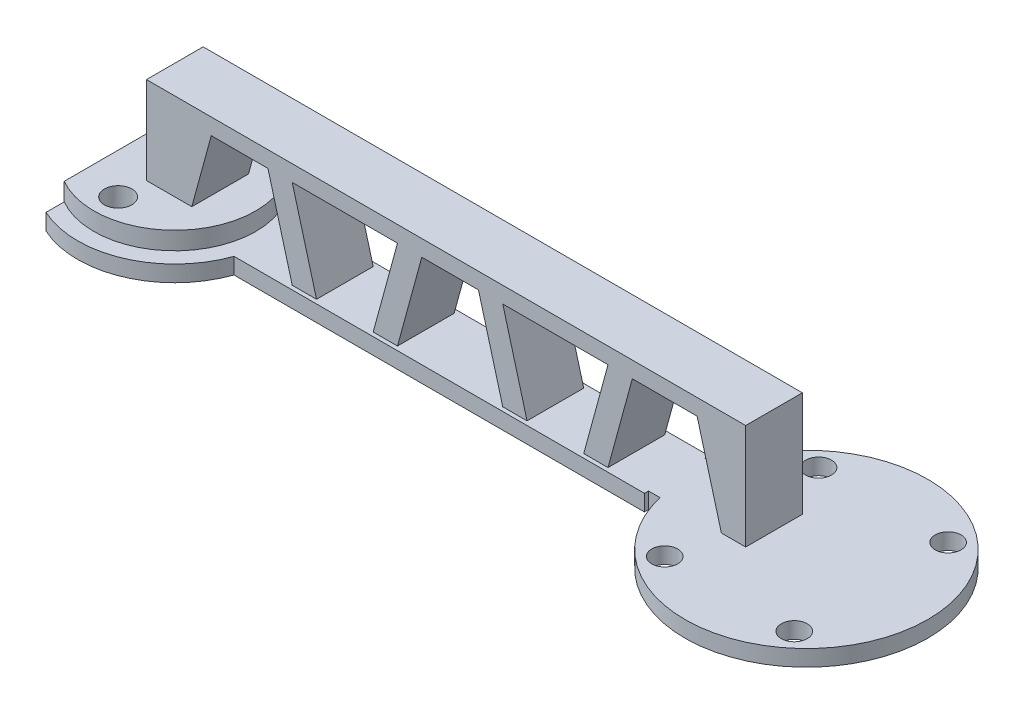
SolidWorks part; units mm, degrees
ref_plane "前视基准面" through (0, 0, 0) normal (0, 0, 1) x (1, 0, 0)
ref_plane "上视基准面" through (0, 0, 0) normal (0, 1, 0) x (1, 0, 0)
ref_plane "右视基准面" through (0, 0, 0) normal (1, 0, 0) x (0, 0, -1)
other "Configuration Table"
sketch "草图1" plane through (0, 0, 0) normal (0, 1, 0) x (1, 0, 0)
  line L0 (0, -4) -> (62, -4)
  line L1 (62, -4) -> (62, 4)
  line L2 (62, 4) -> (0, 4)
  line L3 (0, 4) -> (0, -4)
extrude "凸台-拉伸1" add sketch "草图1" along normal blind 2
sketch "草图2" plane through (0, 0, 0) normal (0, 1, 0) x (1, 0, 0)
  circle A0 centre (0, 0) radius 12
  circle A1 centre (0, -7) radius 1.7
  circle A2 centre (0, 7) radius 1.7
extrude "凸台-拉伸2" add sketch "草图2" along normal blind 2
sketch "草图3" plane through (0, 0, 0) normal (0, 1, 0) x (1, 0, 0)
  circle A0 centre (0, 0) radius 10
  circle A1 centre (0, -7) radius 1.7
  circle A2 centre (0, 7) radius 1.7
extrude "凸台-拉伸3" add sketch "草图3" along normal blind 2.2 from offset 2
sketch "草图4" plane through (0, 0, 0) normal (0, 1, 0) x (1, 0, 0)
  line L0 (-10, -3.5) -> (10, -3.5)
  line L1 (10, -3.5) -> (10, 3.5)
  line L2 (10, 3.5) -> (-10, 3.5)
  line L3 (-10, 3.5) -> (-10, -3.5)
  dimension "D1" = 3.5
  dimension "D2" = 3.5
  dimension "D3" = 10
extrude "凸台-拉伸4" add sketch "草图4" along normal blind 2 from offset 13
sketch "草图5" plane through (0, 0, 0) normal (0, 1, 0) x (1, 0, 0)
  circle A0 centre (78, 0) radius 15
  circle A1 centre (70, -9.5) radius 1.6
  circle A2 centre (70, 9.5) radius 1.6
  circle A3 centre (86, -9.5) radius 1.6
  circle A4 centre (86, 9.5) radius 1.6
extrude "凸台-拉伸5" add sketch "草图5" along normal blind 2
sketch "草图6" plane through (0, 0, 0) normal (0, 0, 1) x (1, 0, 0)
  line L0 (0, 0) -> (74, 0)
  line L1 (74, 0) -> (74, 15)
  line L2 (74, 15) -> (0, 15)
  line L3 (-10, 15) -> (10, 15) construction
  line L4 (0, 15) -> (0, 0)
  line L5 (5, 2) -> (18, 2)
  line L6 (11.3137, 2) -> (-12, 2) construction
  line L7 (11.3137, 2) -> (62, 2) construction
  line L8 (18, 2) -> (15, 13)
  line L9 (15, 13) -> (8, 13)
  line L10 (-10, 13) -> (10, 13) construction
  line L11 (8, 13) -> (5, 2)
  line L12 (18, 13) -> (31, 13)
  line L13 (31, 13) -> (28, 2)
  line L14 (28, 2) -> (21, 2)
  line L15 (21, 2) -> (18, 13)
  line L16 (31, 2) -> (44, 2)
  line L17 (44, 2) -> (41, 13)
  line L18 (41, 13) -> (34, 13)
  line L19 (34, 13) -> (31, 2)
  line L20 (44, 13) -> (57, 13)
  line L21 (57, 13) -> (54, 2)
  line L22 (54, 2) -> (47, 2)
  line L23 (47, 2) -> (44, 13)
  line L24 (57, 2) -> (71, 2)
  line L25 (71.6, 2) -> (68.4, 2) construction
  line L26 (71, 2) -> (68, 13)
  line L27 (68, 13) -> (60, 13)
  line L28 (60, 13) -> (57, 2)
extrude "凸台-拉伸6" add sketch "草图6" along normal blind 7 from offset 3.5
sketch "草图7" plane through (0, 13, 0) normal (0, -1, 0) x (1, 0, 0)
  line L1 (0, 4.7031) -> (-13.8669, 4.7031)
  line L2 (0, 4.7031) -> (0, -4.4889)
  line L3 (0, -4.4889) -> (-13.8669, -4.4889)
  line L4 (-13.8669, 4.7031) -> (-13.8669, -4.4889)
extrude "切除-拉伸1" cut sketch "草图7" against normal blind 10
sketch "草图8" plane through (0, 4.2, 0) normal (0, 1, 0) x (1, 0, 0)
  line L0 (0, -3.5) -> (0, 3.5) construction
  line L1 (-15, 12) -> (-5, 12)
  line L2 (-15, 12) -> (-15, -12)
  line L3 (-15, -12) -> (-5, -12)
  line L4 (-5, 12) -> (-5, -12)
  dimension "D1" = 5
  dimension "D2" = 12
  dimension "D3" = 12
  dimension "D4" = 10
extrude "切除-拉伸2" cut sketch "草图8" against normal blind 10
